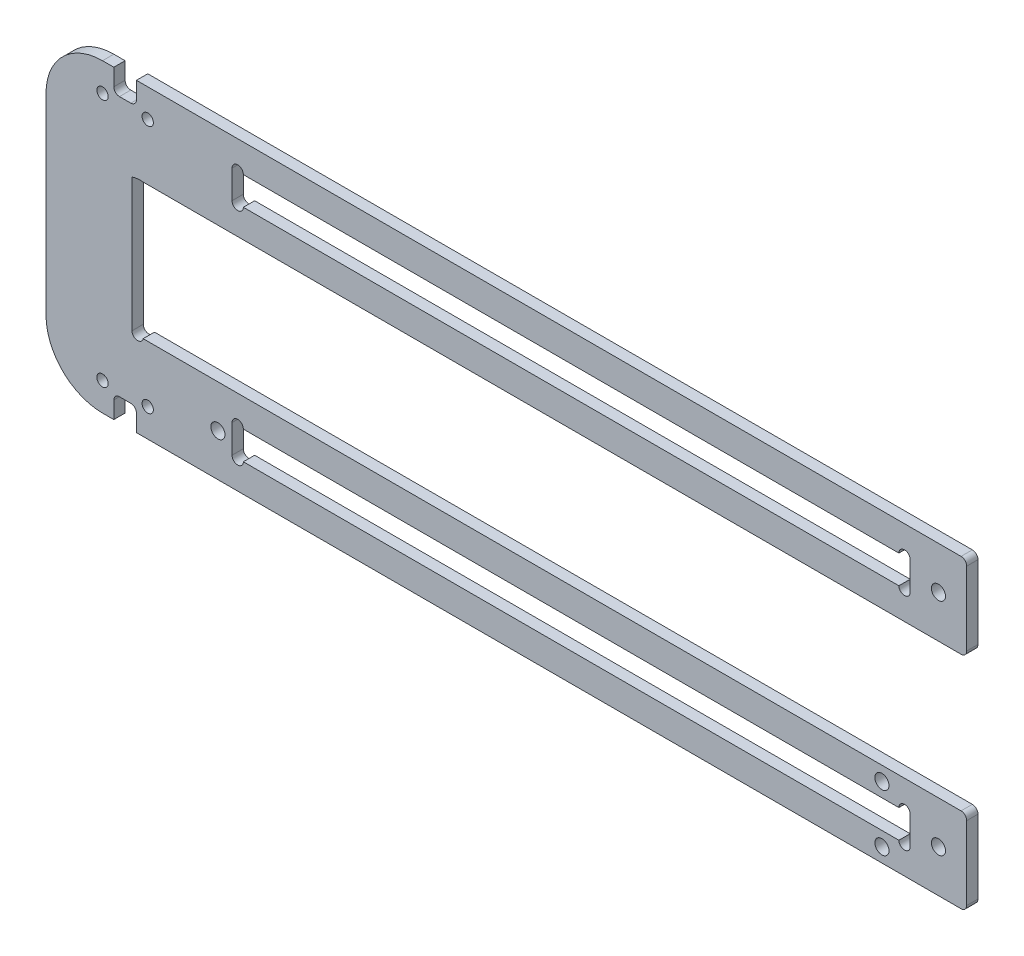
SolidWorks part; units mm, degrees
material "自訂玻璃纖維"
ref_plane "前基準面" through (0, 0, 0) normal (0, 0, 1) x (1, 0, 0)
ref_plane "上基準面" through (0, 0, 0) normal (0, 1, 0) x (1, 0, 0)
ref_plane "右基準面" through (0, 0, 0) normal (1, 0, 0) x (0, 0, -1)
sketch "草圖1" plane through (0, 0, 0) normal (0, 0, 1) x (1, 0, 0)
  line L0 (55.0385, 45.1732) -> (55.0385, 32.1732)
  line L1 (55.0385, 6.1732) -> (55.0385, -6.8268)
  line L2 (-74.9615, -2.8268) -> (-74.9615, 2.1732)
  line L3 (-97.8815, 46.1732) -> (-95.8815, 46.1732)
  line L4 (43.0385, 2.1732) -> (-72.9615, 2.1732)
  line L5 (45.0385, -2.8268) -> (45.0385, 2.1732)
  line L6 (-92.6656, 30.9573) -> (-92.6656, 7.3892)
  line L7 (43.0385, 41.1732) -> (-72.9615, 41.1732)
  line L8 (-107.8815, 36.1732) -> (-107.8815, 2.1732)
  line L9 (43.0385, -2.8268) -> (-72.9615, -2.8268)
  line L10 (54.0385, 31.1732) -> (-90.7636, 31.1732)
  line L11 (45.0385, 41.1732) -> (45.0385, 36.1732)
  line L12 (70.05, 7.3892) -> (70.05, 30.9573) construction
  line L13 (85.266, -7.8268) -> (85.266, 46.1732) construction
  line L14 (-82.6656, 30.9573) -> (-92.6656, 30.9573) construction
  line L15 (70.05, 30.9573) -> (-82.6656, 30.9573) construction
  line L16 (-82.6656, 7.3892) -> (70.05, 7.3892) construction
  line L17 (-82.6656, 7.3892) -> (-92.6656, 7.3892) construction
  line L18 (-82.6656, -7.8268) -> (85.266, -7.8268) construction
  line L19 (-82.6656, -7.8268) -> (-97.8815, -7.8268) construction
  line L20 (-82.6656, 46.1732) -> (-97.8815, 46.1732) construction
  line L21 (85.266, 46.1732) -> (-82.6656, 46.1732) construction
  line L22 (43.0385, 36.1732) -> (-72.9615, 36.1732)
  line L23 (-74.9615, 41.1732) -> (-74.9615, 36.1732)
  line L24 (54.0385, 7.1732) -> (-90.6892, 7.1732)
  line L25 (-97.8815, -7.8268) -> (-95.8815, -7.8268)
  line L26 (-94.8815, 42.1732) -> (-92.8815, 42.1732)
  line L27 (-91.8815, 46.1732) -> (54.0385, 46.1732)
  line L28 (-107.8815, 36.1732) -> (-107.8815, 2.1732) construction
  line L29 (-92.6656, 30.9573) -> (-92.6656, 7.3892) construction
  line L30 (-95.8815, 43.1732) -> (-95.8815, 46.1732)
  line L31 (-91.8815, -7.8268) -> (54.0385, -7.8268)
  line L32 (-91.8815, 43.1732) -> (-91.8815, 46.1732)
  line L33 (-91.8815, -4.8268) -> (-91.8815, -7.8268)
  line L34 (-95.8815, -4.8268) -> (-95.8815, -7.8268)
  line L35 (-94.8815, -3.8268) -> (-92.8815, -3.8268)
  circle A0 centre (-97.8815, 41.1732) radius 1
  arc A1 (-97.8815, 46.1732) -> (-107.8815, 36.1732) centre (-97.8815, 36.1732) ccw
  arc A2 (-92.6656, 30.9573) -> (-92.6656, 30.9573) centre (-92.6656, 30.9573) ccw
  circle A3 centre (-89.8815, 41.1732) radius 1
  arc A4 (45.0385, 41.1732) -> (43.0385, 41.1732) centre (44.0385, 41.1732) ccw
  arc A5 (45.0385, 36.1732) -> (43.0385, 36.1732) centre (44.0385, 36.1732) cw
  arc A6 (-74.9615, 41.1732) -> (-72.9615, 41.1732) centre (-73.9615, 41.1732) cw
  arc A7 (-74.9615, 36.1732) -> (-72.9615, 36.1732) centre (-73.9615, 36.1732) ccw
  arc A8 (-92.6656, 7.3892) -> (-90.6892, 7.1732) centre (-91.6656, 7.3892) ccw
  arc A9 (55.0385, -6.8268) -> (54.0385, -7.8268) centre (54.0385, -6.8268) cw
  arc A10 (55.0385, 6.1732) -> (54.0385, 7.1732) centre (54.0385, 6.1732) ccw
  arc A11 (-74.9615, 2.1732) -> (-72.9615, 2.1732) centre (-73.9615, 2.1732) cw
  arc A12 (-74.9615, -2.8268) -> (-72.9615, -2.8268) centre (-73.9615, -2.8268) ccw
  arc A13 (55.0385, 45.1732) -> (54.0385, 46.1732) centre (54.0385, 45.1732) ccw
  arc A14 (55.0385, 32.1732) -> (54.0385, 31.1732) centre (54.0385, 32.1732) cw
  arc A15 (-92.6656, 30.9573) -> (-90.7636, 31.1732) centre (-91.236, 26.8497) cw
  arc A16 (45.0385, 2.1732) -> (43.0385, 2.1732) centre (44.0385, 2.1732) ccw
  arc A17 (45.0385, -2.8268) -> (43.0385, -2.8268) centre (44.0385, -2.8268) cw
  circle A18 centre (-89.8815, -2.8268) radius 1
  arc A19 (-97.8815, -7.8268) -> (-107.8815, 2.1732) centre (-97.8815, 2.1732) cw construction
  arc A20 (-92.6656, 7.3892) -> (-92.6656, 7.3892) centre (-92.6656, 7.3892) cw construction
  arc A21 (-97.8815, -7.8268) -> (-107.8815, 2.1732) centre (-97.8815, 2.1732) cw
  circle A22 centre (-97.8815, -2.8268) radius 1
  circle A23 centre (50.0385, 38.6732) radius 1.25
  circle A24 centre (50.0385, -0.3268) radius 1.25
  arc A25 (-95.8815, 43.1732) -> (-94.8815, 42.1732) centre (-94.8815, 43.1732) ccw
  arc A26 (-92.8815, 42.1732) -> (-91.8815, 43.1732) centre (-92.8815, 43.1732) ccw
  arc A27 (-92.8815, -3.8268) -> (-91.8815, -4.8268) centre (-92.8815, -4.8268) cw
  arc A28 (-95.8815, -4.8268) -> (-94.8815, -3.8268) centre (-94.8815, -4.8268) cw
  point P45 (55.0385, -7.8268)
  point P51 (55.0385, 7.1732)
  point P76 (55.0385, 46.1732)
  point P79 (55.0385, 31.1732)
  dimension "D4" = 10
  dimension "D7" = 4
  dimension "D8" = 2.5
  dimension "D9" = 1
  dimension "D10" = 5
  dimension "D2" = 8
  dimension "D6" = 2
  dimension "D11" = 2.5
  dimension "D12" = 5
  dimension "D13" = 5
  dimension "D17" = 13
  dimension "D18" = 1
  dimension "D3" = 7.5
  dimension "D14" = 7.5
  dimension "D5" = 120
  dimension "D15" = 3
  dimension "D16" = 24
  dimension "D19" = 0
  dimension "D20" = 0
  dimension "D21" = 0
  dimension "D22" = 2
extrude "填料-伸長2" add sketch "草圖1" along normal blind 2
sketch "草圖2" plane through (0, 0, 2) normal (0, 0, 1) x (1, 0, 0)
  line L0 (43.0385, 2.1732) -> (-72.9615, 2.1732) construction
  line L1 (-74.9615, -2.8268) -> (-74.9615, 2.1732) construction
  line L4 (54.0385, 7.1732) -> (-90.6892, 7.1732) construction
  line L5 (-97.8815, -7.8268) -> (-95.8815, -7.8268) construction
  line L7 (45.0385, -2.8268) -> (45.0385, 2.1732) construction
  circle A0 centre (-77.4615, -0.3268) radius 1.25
  circle A1 centre (40.0385, 4.6732) radius 1.25
  circle A2 centre (40.0385, -5.3268) radius 1.25
  dimension "D1" = 2.5
  dimension "D2" = 2.5
  dimension "D3" = 2.5
  dimension "D4" = 2.5
  dimension "D5" = 2.5
  dimension "D6" = 2.5
  dimension "D7" = 2.5
  dimension "D8" = 5
  dimension "D9" = 5
extrude "除料-伸長1" cut sketch "草圖2" against normal blind 10
